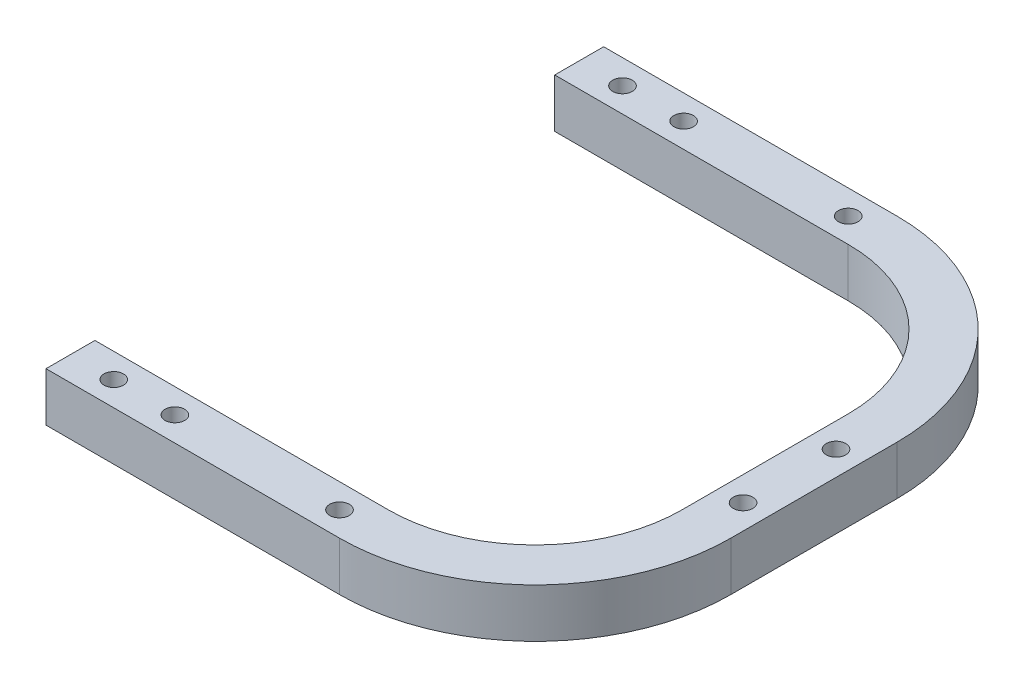
SolidWorks part; units mm, degrees
ref_plane "Front Plane" through (0, 0, 0) normal (0, 0, 1) x (1, 0, 0)
ref_plane "Top Plane" through (0, 0, 0) normal (0, 1, 0) x (1, 0, 0)
ref_plane "Right Plane" through (0, 0, 0) normal (1, 0, 0) x (0, 0, -1)
sketch "Sketch1" plane through (0, 0, 0) normal (0, 1, 0) x (1, 0, 0)
  line L0 (50, 0) -> (60, 0) construction
  line L1 (20, -47) -> (-40, -47)
  line L2 (-40, -47) -> (-40, -57)
  line L3 (-40, -57) -> (20, -57)
  line L4 (20, 47) -> (-40, 47)
  line L5 (-40, 47) -> (-40, 57)
  line L6 (-40, 57) -> (20, 57)
  line L7 (50, 17) -> (50, -17)
  line L8 (60, 17) -> (60, -17)
  line L9 (0, 0) -> (50, 0) construction
  line L10 (20, 47) -> (20, -47) construction
  line L11 (60, 17) -> (50, 17) construction
  line L12 (60, -17) -> (50, -17) construction
  line L13 (55, 17) -> (55, 9.5) construction
  line L14 (55, 9.5) -> (55, -9.5) construction
  line L15 (55, -9.5) -> (55, -17) construction
  line L16 (20, 57) -> (10, 47) construction
  line L17 (20, -47) -> (10, -57) construction
  line L18 (10, 47) -> (10, 57) construction
  line L19 (10, -57) -> (10, -47) construction
  arc A2 (20, 47) -> (50, 17) centre (20, 17) cw
  arc A3 (20, -47) -> (50, -17) centre (20, -17) ccw
  arc A4 (20, -57) -> (60, -17) centre (20, -17) ccw
  arc A5 (20, 57) -> (60, 17) centre (20, 17) cw
  circle A6 centre (55, 9.5) radius 2
  circle A7 centre (55, -9.5) radius 2
  circle A8 centre (15, 52) radius 2
  circle A9 centre (15, -52) radius 2
  circle A10 centre (-18.6515, 52) radius 2
  circle A11 centre (-31.1515, 52) radius 2
  circle A12 centre (-18.6515, -52) radius 2
  circle A13 centre (-31.1515, -52) radius 2
  point P15 (50, 0)
  point P16 (60, 0)
  point P35 (15, 52)
  point P36 (15, -52)
  dimension "D6" = 4
  dimension "D1" = 10
  dimension "D2" = 94
  dimension "D3" = 60
  dimension "D4" = 50
  dimension "D5" = 20
  dimension "D7" = 7.5
extrude "Boss-Extrude1" add sketch "Sketch1" along normal blind 10
